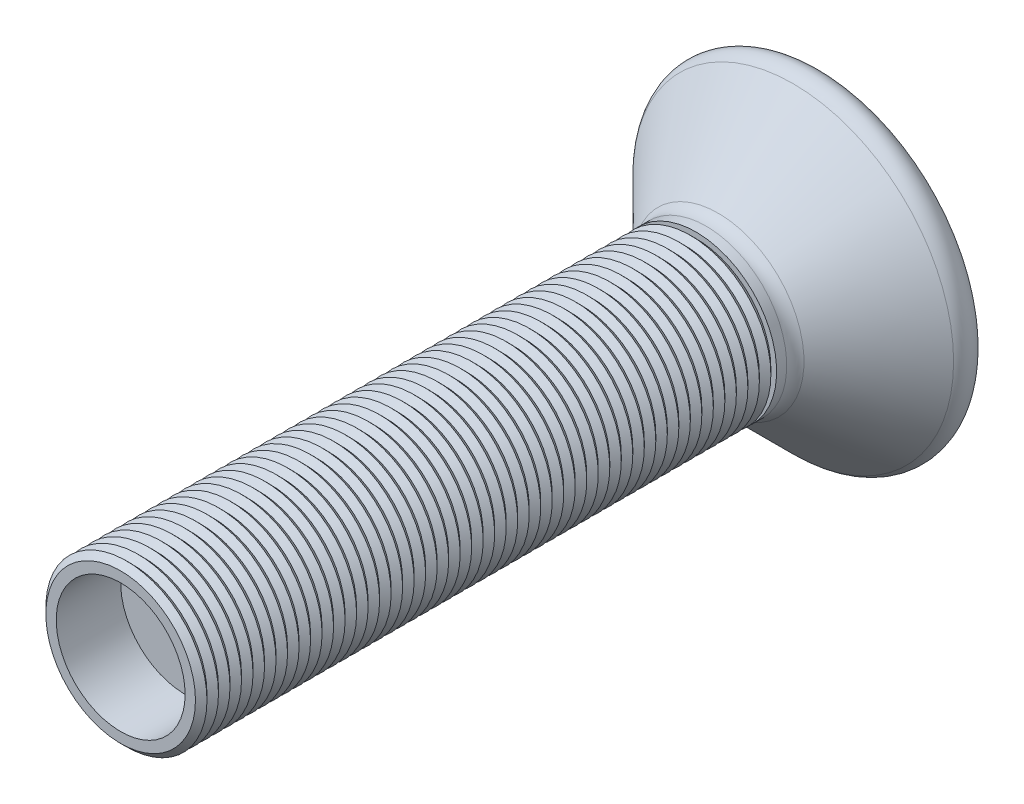
SolidWorks part; units mm, degrees
ref_plane "Alzado" through (0, 0, 0) normal (0, 0, 1) x (1, 0, 0)
ref_plane "Planta" through (0, 0, 0) normal (0, 1, 0) x (1, 0, 0)
ref_plane "Vista lateral" through (0, 0, 0) normal (1, 0, 0) x (0, 0, -1)
ref_plane "Plano1" through (0, 0, 0) normal (0, -1, 0) x (1, 0, 0)
sketch "Croquis1" plane through (0, 0, 0) normal (0, -1, 0) x (1, 0, 0)
  line L0 (14, 22) -> (0, 22)
  line L1 (0, 22) -> (0, 0)
  line L2 (0, 0) -> (33, 0)
  line L3 (33, 0) -> (14, 19)
  line L4 (14, 19) -> (14, 22)
  line L5 (0, 22) -> (0, 0) construction
  dimension "D1" = 14
  dimension "D2" = 22
  dimension "D3" = 3
  dimension "D5" = 45
revolve "Revolución1" add sketch "Croquis1" angle 360 about L5
sketch "Croquis2" plane through (0, 0, 22) normal (0, 0, 1) x (1, 0, 0)
  circle A0 centre (0, 0) radius 13
  dimension "D1" = 26
extrude "Saliente-Extruir1" add sketch "Croquis2" along normal blind 100
fillet "Redondeo1" radius 3 2 edges at (-14, 0, 19) (-33, 0, 0)
sketch "Croquis6" plane through (0, 0, 0) normal (1, 0, 0) x (0, 0, -1)
  line L0 (-23, 14) -> (-22, 13)
  line L1 (-23, 14) -> (-24, 13)
  line L2 (-22, 13) -> (-122, 13) construction
  line L3 (-22, 14) -> (-22, -14) construction
  line L4 (-24, 13) -> (-22, 13)
  line L5 (-25, 14) -> (-24, 13)
  line L6 (-25, 14) -> (-26, 13)
  line L7 (-26, 13) -> (-24, 13)
  line L8 (-27, 14) -> (-26, 13)
  line L9 (-27, 14) -> (-28, 13)
  line L10 (-28, 13) -> (-26, 13)
  line L11 (-29, 14) -> (-28, 13)
  line L12 (-29, 14) -> (-30, 13)
  line L13 (-30, 13) -> (-28, 13)
  line L14 (-31, 14) -> (-30, 13)
  line L15 (-31, 14) -> (-32, 13)
  line L16 (-32, 13) -> (-30, 13)
  line L17 (-33, 14) -> (-32, 13)
  line L18 (-33, 14) -> (-34, 13)
  line L19 (-34, 13) -> (-32, 13)
  line L20 (-35, 14) -> (-34, 13)
  line L21 (-35, 14) -> (-36, 13)
  line L22 (-36, 13) -> (-34, 13)
  line L23 (-37, 14) -> (-36, 13)
  line L24 (-37, 14) -> (-38, 13)
  line L25 (-38, 13) -> (-36, 13)
  line L26 (-39, 14) -> (-38, 13)
  line L27 (-39, 14) -> (-40, 13)
  line L28 (-40, 13) -> (-38, 13)
  line L29 (-41, 14) -> (-40, 13)
  line L30 (-41, 14) -> (-42, 13)
  line L31 (-42, 13) -> (-40, 13)
  line L32 (-43, 14) -> (-42, 13)
  line L33 (-43, 14) -> (-44, 13)
  line L34 (-44, 13) -> (-42, 13)
  line L35 (-45, 14) -> (-44, 13)
  line L36 (-45, 14) -> (-46, 13)
  line L37 (-46, 13) -> (-44, 13)
  line L38 (-47, 14) -> (-46, 13)
  line L39 (-47, 14) -> (-48, 13)
  line L40 (-48, 13) -> (-46, 13)
  line L41 (-49, 14) -> (-48, 13)
  line L42 (-49, 14) -> (-50, 13)
  line L43 (-50, 13) -> (-48, 13)
  line L44 (-51, 14) -> (-50, 13)
  line L45 (-51, 14) -> (-52, 13)
  line L46 (-52, 13) -> (-50, 13)
  line L47 (-53, 14) -> (-52, 13)
  line L48 (-53, 14) -> (-54, 13)
  line L49 (-54, 13) -> (-52, 13)
  line L50 (-55, 14) -> (-54, 13)
  line L51 (-55, 14) -> (-56, 13)
  line L52 (-56, 13) -> (-54, 13)
  line L53 (-57, 14) -> (-56, 13)
  line L54 (-57, 14) -> (-58, 13)
  line L55 (-58, 13) -> (-56, 13)
  line L56 (-59, 14) -> (-58, 13)
  line L57 (-59, 14) -> (-60, 13)
  line L58 (-60, 13) -> (-58, 13)
  line L59 (-61, 14) -> (-60, 13)
  line L60 (-61, 14) -> (-62, 13)
  line L61 (-62, 13) -> (-60, 13)
  line L62 (-63, 14) -> (-62, 13)
  line L63 (-63, 14) -> (-64, 13)
  line L64 (-64, 13) -> (-62, 13)
  line L65 (-65, 14) -> (-64, 13)
  line L66 (-65, 14) -> (-66, 13)
  line L67 (-66, 13) -> (-64, 13)
  line L68 (-67, 14) -> (-66, 13)
  line L69 (-67, 14) -> (-68, 13)
  line L70 (-68, 13) -> (-66, 13)
  line L71 (-69, 14) -> (-68, 13)
  line L72 (-69, 14) -> (-70, 13)
  line L73 (-70, 13) -> (-68, 13)
  line L74 (-71, 14) -> (-70, 13)
  line L75 (-71, 14) -> (-72, 13)
  line L76 (-72, 13) -> (-70, 13)
  line L77 (-73, 14) -> (-72, 13)
  line L78 (-73, 14) -> (-74, 13)
  line L79 (-74, 13) -> (-72, 13)
  line L80 (-75, 14) -> (-74, 13)
  line L81 (-75, 14) -> (-76, 13)
  line L82 (-76, 13) -> (-74, 13)
  line L83 (-77, 14) -> (-76, 13)
  line L84 (-77, 14) -> (-78, 13)
  line L85 (-78, 13) -> (-76, 13)
  line L86 (-79, 14) -> (-78, 13)
  line L87 (-79, 14) -> (-80, 13)
  line L88 (-80, 13) -> (-78, 13)
  line L89 (-81, 14) -> (-80, 13)
  line L90 (-81, 14) -> (-82, 13)
  line L91 (-82, 13) -> (-80, 13)
  line L92 (-83, 14) -> (-82, 13)
  line L93 (-83, 14) -> (-84, 13)
  line L94 (-84, 13) -> (-82, 13)
  line L95 (-85, 14) -> (-84, 13)
  line L96 (-85, 14) -> (-86, 13)
  line L97 (-86, 13) -> (-84, 13)
  line L98 (-87, 14) -> (-86, 13)
  line L99 (-87, 14) -> (-88, 13)
  line L100 (-88, 13) -> (-86, 13)
  line L101 (-89, 14) -> (-88, 13)
  line L102 (-89, 14) -> (-90, 13)
  line L103 (-90, 13) -> (-88, 13)
  line L104 (-91, 14) -> (-90, 13)
  line L105 (-91, 14) -> (-92, 13)
  line L106 (-92, 13) -> (-90, 13)
  line L107 (-93, 14) -> (-92, 13)
  line L108 (-93, 14) -> (-94, 13)
  line L109 (-94, 13) -> (-92, 13)
  line L110 (-95, 14) -> (-94, 13)
  line L111 (-95, 14) -> (-96, 13)
  line L112 (-96, 13) -> (-94, 13)
  line L113 (-97, 14) -> (-96, 13)
  line L114 (-97, 14) -> (-98, 13)
  line L115 (-98, 13) -> (-96, 13)
  line L116 (-99, 14) -> (-98, 13)
  line L117 (-99, 14) -> (-100, 13)
  line L118 (-100, 13) -> (-98, 13)
  line L119 (-101, 14) -> (-100, 13)
  line L120 (-101, 14) -> (-102, 13)
  line L121 (-102, 13) -> (-100, 13)
  line L122 (-103, 14) -> (-102, 13)
  line L123 (-103, 14) -> (-104, 13)
  line L124 (-104, 13) -> (-102, 13)
  line L125 (-105, 14) -> (-104, 13)
  line L126 (-105, 14) -> (-106, 13)
  line L127 (-106, 13) -> (-104, 13)
  line L128 (-107, 14) -> (-106, 13)
  line L129 (-107, 14) -> (-108, 13)
  line L130 (-108, 13) -> (-106, 13)
  line L131 (-109, 14) -> (-108, 13)
  line L132 (-109, 14) -> (-110, 13)
  line L133 (-110, 13) -> (-108, 13)
  line L134 (-111, 14) -> (-110, 13)
  line L135 (-111, 14) -> (-112, 13)
  line L136 (-112, 13) -> (-110, 13)
  line L137 (-113, 14) -> (-112, 13)
  line L138 (-113, 14) -> (-114, 13)
  line L139 (-114, 13) -> (-112, 13)
  line L140 (-115, 14) -> (-114, 13)
  line L141 (-115, 14) -> (-116, 13)
  line L142 (-116, 13) -> (-114, 13)
  line L143 (-117, 14) -> (-116, 13)
  line L144 (-117, 14) -> (-118, 13)
  line L145 (-118, 13) -> (-116, 13)
  line L146 (-119, 14) -> (-118, 13)
  line L147 (-119, 14) -> (-120, 13)
  line L148 (-120, 13) -> (-118, 13)
  line L149 (-121, 14) -> (-120, 13)
  line L150 (-121, 14) -> (-122, 13)
  line L151 (-122, 13) -> (-120, 13)
  point P0 (-22, 13)
  dimension "D1" = 1
  dimension "D2" = 45
  dimension "D3" = 45
  dimension "D4" = 50
ref_axis "Eje1" through (0, 0, 122) along (0, 0, -1)
revolve "Revolución2" add sketch "Croquis6" angle 360 about axis through (0, 0, 122) along (0, 0, -1)
sketch "Croquis8" plane through (0, 0, 122) normal (0, 0, 1) x (1, 0, 0)
  circle A0 centre (0, 0) radius 11.2
  dimension "D1" = 22.4
extrude "Cortar-Extruir1" cut sketch "Croquis8" against normal blind 11.2
sketch "Croquis9" plane through (0, 0, 0) normal (0, 0, -1) x (-1, 0, 0)
  circle A0 centre (0, 0) radius 11.2 construction
  circle A1 centre (0, 0) radius 11.2
extrude "Cortar-Extruir2" cut sketch "Croquis9" against normal blind 11.2
sketch "Croquis10" plane through (0, 0, 11.2) normal (0, 0, -1) x (-1, 0, 0)
  circle A0 centre (0, 0) radius 4.5
  dimension "D1" = 9
extrude "Cortar-Extruir3" cut sketch "Croquis10" against normal up to next
